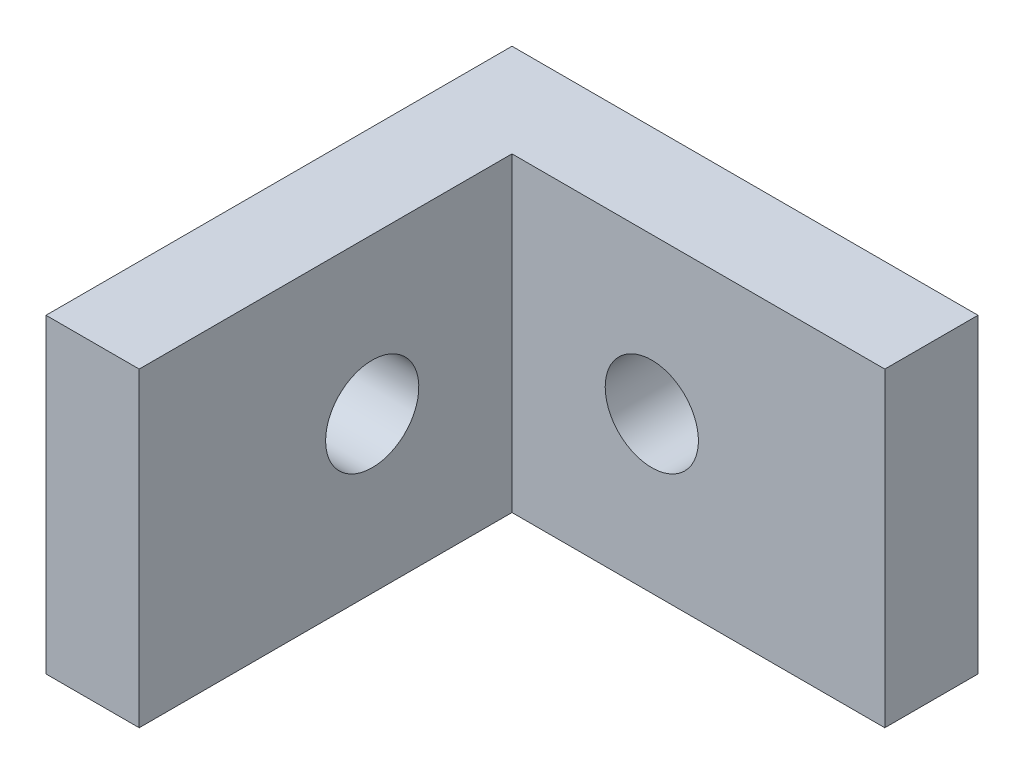
SolidWorks part; units mm, degrees
ref_plane "前视基准面" through (0, 0, 0) normal (0, 0, 1) x (1, 0, 0)
ref_plane "上视基准面" through (0, 0, 0) normal (0, 1, 0) x (1, 0, 0)
ref_plane "右视基准面" through (0, 0, 0) normal (1, 0, 0) x (0, 0, -1)
other "Configuration Table"
sketch "草图1" plane through (0, 0, 0) normal (0, 0, 1) x (1, 0, 0)
  line L1 (-7.5, -5) -> (7.5, -5)
  line L2 (-7.5, -5) -> (-7.5, 5)
  line L3 (-7.5, 5) -> (7.5, 5)
  line L4 (7.5, -5) -> (7.5, 5)
  line L5 (0, 5) -> (0, -5) construction
  line L6 (-7.5, 0) -> (7.5, 0) construction
  point P0 (0, 0)
  dimension "D1" = 10
  dimension "D2" = 15
extrude "凸台-拉伸1" add sketch "草图1" along normal blind 3
sketch "草图2" plane through (0, 0, 3) normal (0, 0, 1) x (1, 0, 0)
  line L0 (-7.5, -5) -> (7.5, -5) construction
  line L1 (-7.5, 5) -> (-4.5, 5)
  line L2 (-7.5, 5) -> (-7.5, -5)
  line L3 (-7.5, -5) -> (-4.5, -5)
  line L4 (-4.5, 5) -> (-4.5, -5)
  dimension "D1" = 3
extrude "凸台-拉伸2" add sketch "草图2" along normal blind 12
sketch "草图3" plane through (0, 0, 0) normal (0, 0, -1) x (-1, 0, 0)
  circle A0 centre (0, 0) radius 1.5
  dimension "D1" = 3
extrude "切除-拉伸1" cut sketch "草图3" against normal blind 7
sketch "草图4" plane through (-7.5, 0, 0) normal (-1, 0, 0) x (0, 0, 1)
  line L0 (15, 5) -> (0, 5) construction
  circle A0 centre (7.5, 0) radius 1.5
  point P2 (0, 0)
  point P4 (0, 0)
  point P7 (7.5, 5)
  dimension "D1" = 3
extrude "切除-拉伸2" cut sketch "草图4" against normal blind 7
